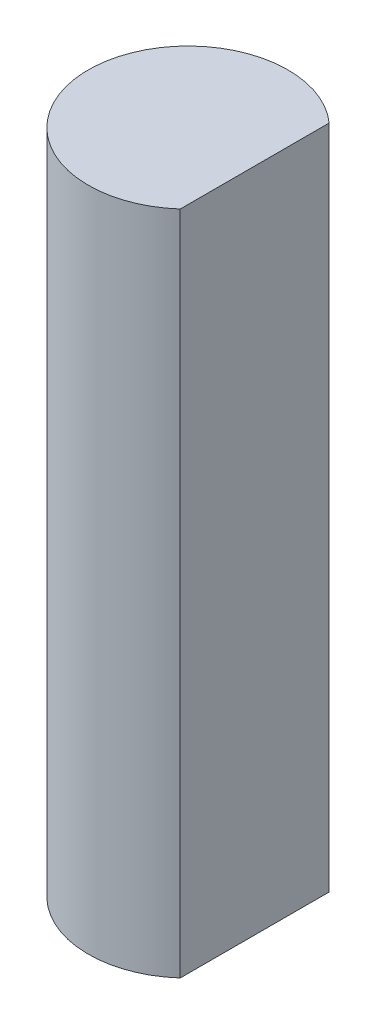
SolidWorks part; units mm, degrees
ref_plane "Front Plane" through (0, 0, 0) normal (0, 0, 1) x (1, 0, 0)
ref_plane "Top Plane" through (0, 0, 0) normal (0, 1, 0) x (1, 0, 0)
ref_plane "Right Plane" through (0, 0, 0) normal (1, 0, 0) x (0, 0, -1)
sketch "Sketch1" plane through (0, 0, 0) normal (0, 1, 0) x (1, 0, 0)
  line L0 (1, 1.118) -> (1, -1.118)
  line L1 (1, -1.118) -> (1.0118, -1.1448)
  line L2 (0, 0) -> (1.5, 0) construction
  line L4 (1.5, 1.0987) -> (1.5, -1.0323) construction
  arc A0 (1, 1.118) -> (1, -1.118) centre (0, 0) ccw
  circle A1 centre (0, 0) radius 1.5 construction
  dimension "D1" = 1.5
  dimension "D2" = 0.5
extrude "Boss-Extrude1" add sketch "Sketch1" along normal blind 10 contours L0 A0
